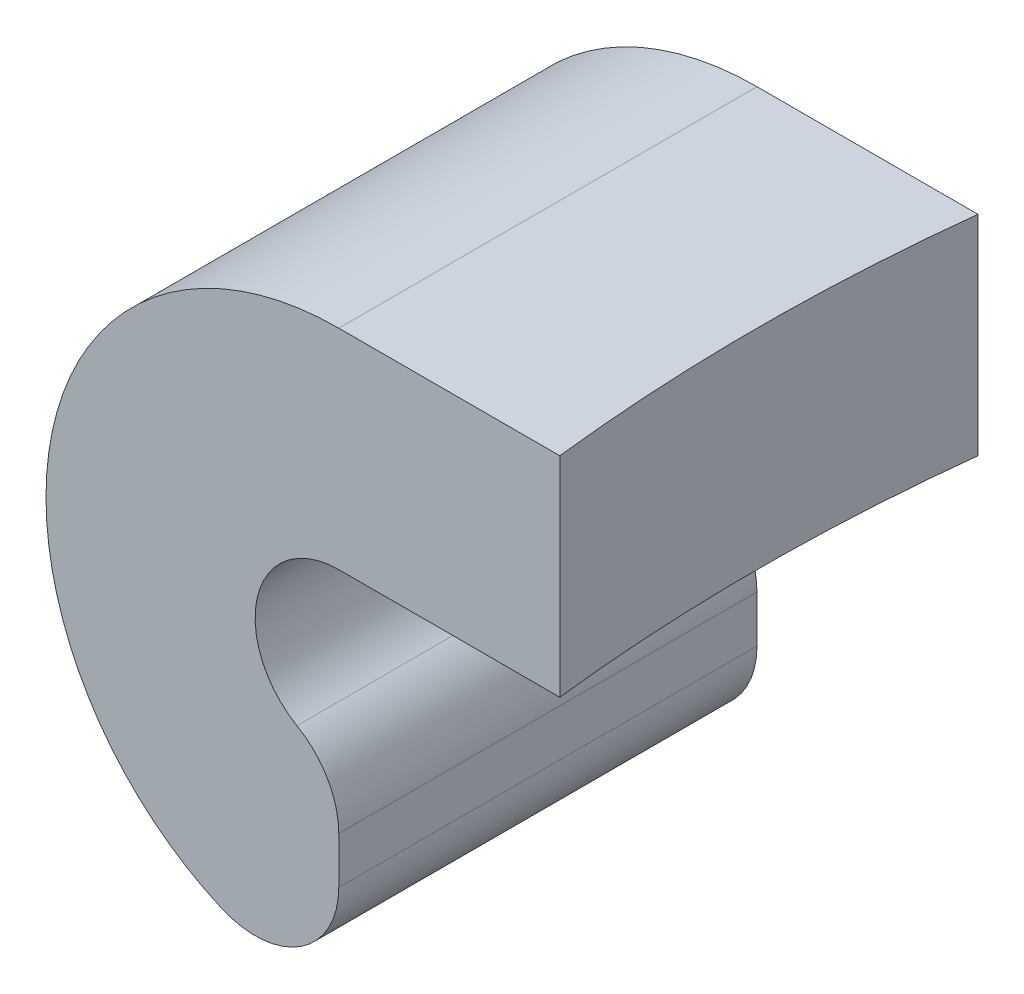
SolidWorks part; units mm, degrees
ref_plane "Front Plane" through (0, 0, 0) normal (0, 0, 1) x (1, 0, 0)
ref_plane "Top Plane" through (0, 0, 0) normal (0, 1, 0) x (1, 0, 0)
ref_plane "Right Plane" through (0, 0, 0) normal (1, 0, 0) x (0, 0, -1)
sketch "Sketch1" plane through (0, 0, 0) normal (0, 0, 1) x (1, 0, 0)
  line L4 (0, -2.7321) -> (0, -3.2913)
  line L5 (0, 2.5) -> (6.7539, 2.5)
  line L7 (0, 0) -> (6.7539, 0)
  line L8 (6.7539, 2.5) -> (6.7539, 0)
  arc A0 (0, 2.5) -> (-1.4, -4.2078) centre (0, -1) ccw
  arc A1 (0, 0) -> (-0.5, -1.866) centre (0, -1) ccw
  arc A2 (-1.4, -4.2078) -> (0, -3.2913) centre (-1, -3.2913) ccw
  arc A3 (-0.5, -1.866) -> (0, -2.7321) centre (-1, -2.7321) cw
  point P1 (-2.4293, -3.5196)
  point P4 (-0.8068, -1.5908)
  point P14 (-0.5377, -1.8431)
  dimension "D2" = 2.5
  dimension "D3" = 1
  dimension "D1" = 1
extrude "Boss-Extrude1" add sketch "Sketch1" along normal mid plane 5
sketch "Sketch2" plane through (0, 0, 0) normal (0, 1, 0) x (1, 0, 0)
  line L1 (2.5, 0) -> (2.5, -3.9522) construction
  circle A0 centre (24.5, 0) radius 22
  dimension "D1" = 44
  dimension "D2" = 2.5
extrude "Cut-Extrude1" cut sketch "Sketch2" along normal through all
equation "\"in_d\"=40"
equation "\"pipe_thick\"=2"
equation "\"rod_angle\"=20"
equation "\"rod_radius\"=33.5"
equation "\"rod_diameter\"=8"
equation "\"lin_bear_h\"=24"
equation "\"screw_radius\"=40"
equation "\"screw_angle\"=50"
equation "\"lin_bearing_d\"=15"
equation "\"drill_rod_pair\"=37"
equation "\"support_rod_w\"=50"
equation "\"vertical_slider_w\"=65"
equation "\"vertical_slider_d\"=20"
equation "\"slope_angle\"=30"
equation "\"D1@Sketch2\"=\"pipe_thick\"*2+\"in_d\""
